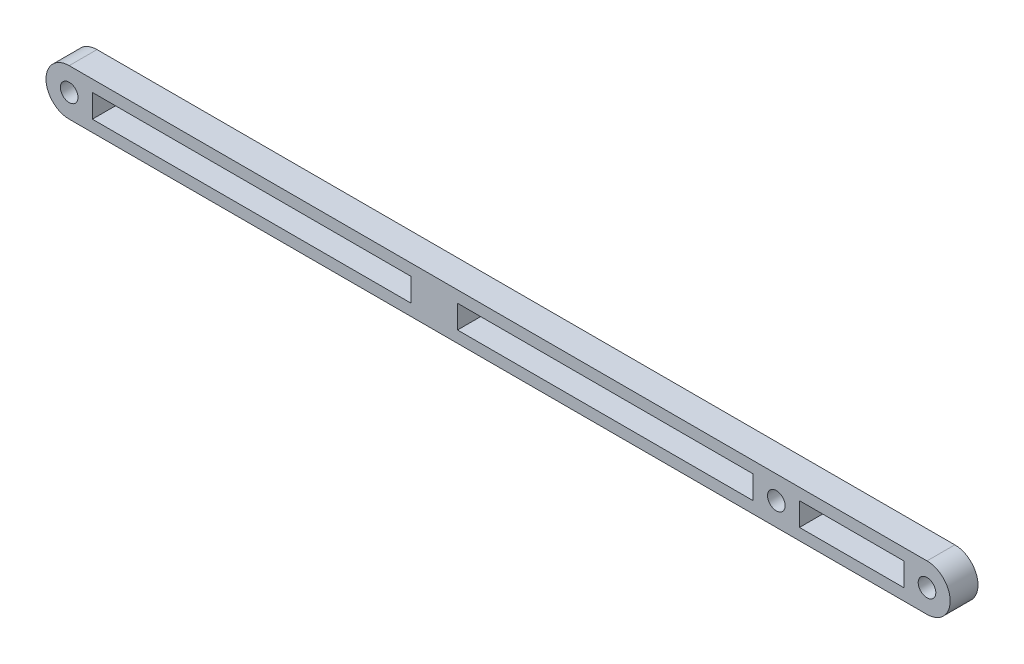
SolidWorks part; units mm, degrees
material "MDF"
ref_plane "Front Plane" through (0, 0, 0) normal (0, 0, 1) x (1, 0, 0)
ref_plane "Top Plane" through (0, 0, 0) normal (0, 1, 0) x (1, 0, 0)
ref_plane "Right Plane" through (0, 0, 0) normal (1, 0, 0) x (0, 0, -1)
sketch "Sketch1" plane through (0, 0, 0) normal (0, 0, 1) x (1, 0, 0)
  line L0 (0, -5) -> (0, 5) construction
  line L1 (-92.5, 5) -> (92.5, 5)
  line L2 (-92.5, -5) -> (92.5, -5)
  line L3 (92.5, 0) -> (-92.5, 0) construction
  line L4 (0, 0) -> (60, 0) construction
  arc A0 (92.5, 5) -> (92.5, -5) centre (92.5, 0) cw
  arc A1 (-92.5, 5) -> (-92.5, -5) centre (-92.5, 0) ccw
  circle A2 centre (-92.5, 0) radius 1.9
  circle A3 centre (92.5, 0) radius 1.9
  circle A4 centre (60, 0) radius 1.9
  point P4 (0, 0)
  point P8 (0, 5)
  point P11 (0, -5)
  point P13 (0, 0)
  dimension "D3" = 3.8
  dimension "D4" = 3.8
  dimension "D5" = 3.8
  dimension "D1" = 10
  dimension "D2" = 185
  dimension "D6" = 60
extrude "Boss-Extrude1" add sketch "Sketch1" along normal blind 6
sketch "Sketch2" plane through (0, 0, 6) normal (0, 0, 1) x (1, 0, 0)
  line L0 (92.5, 5) -> (-92.5, 5) construction
  line L1 (-92.5, 1.9) -> (-92.5, -1.9) construction
  line L2 (-87.5, -2.5) -> (55, -2.5)
  line L3 (-87.5, -2.5) -> (-87.5, 2.5)
  line L4 (-87.5, 2.5) -> (55, 2.5)
  line L5 (55, -2.5) -> (55, 2.5)
  line L6 (-87.5, -2.5) -> (55, 2.5) construction
  line L7 (-87.5, 2.5) -> (55, -2.5) construction
  line L8 (65, -2.5) -> (87.5, -2.5)
  line L9 (65, -2.5) -> (65, 2.5)
  line L10 (65, 2.5) -> (87.5, 2.5)
  line L11 (87.5, -2.5) -> (87.5, 2.5)
  line L12 (65, -2.5) -> (87.5, 2.5) construction
  line L13 (65, 2.5) -> (87.5, -2.5) construction
  line L14 (92.5, 1.9) -> (92.5, -1.9) construction
  line L15 (60, 1.9) -> (60, -1.9) construction
  circle A0 centre (-92.5, 0) radius 1.9 construction
  circle A1 centre (92.5, 0) radius 1.9 construction
  circle A2 centre (60, 0) radius 1.9 construction
  point P4 (0, 0)
  dimension "D1" = 5
  dimension "D2" = 5
  dimension "D3" = 5
  dimension "D4" = 5
  dimension "D5" = 5
  dimension "D6" = 5
  dimension "D7" = 2.5
  dimension "D8" = 2.5
extrude "Cut-Extrude1" cut sketch "Sketch2" against normal through all
sketch "Sketch3" plane through (0, 0, 6) normal (0, 0, 1) x (1, 0, 0)
  line L0 (55, 2.5) -> (-87.5, 2.5) construction
  line L1 (-18.75, 2.5) -> (-8.75, 2.5)
  line L2 (-18.75, 2.5) -> (-18.75, -2.5)
  line L3 (-18.75, -2.5) -> (-8.75, -2.5)
  line L4 (-8.75, 2.5) -> (-8.75, -2.5)
  line L5 (-18.75, 2.5) -> (-8.75, -2.5) construction
  line L6 (-18.75, -2.5) -> (-8.75, 2.5) construction
  line L7 (-87.5, -2.5) -> (55, -2.5) construction
  line L8 (-87.5, 2.5) -> (-87.5, -2.5) construction
  point P4 (-13.75, 0)
  dimension "D1" = 68.75
  dimension "D2" = 10
extrude "Boss-Extrude2" add sketch "Sketch3" against normal through all
